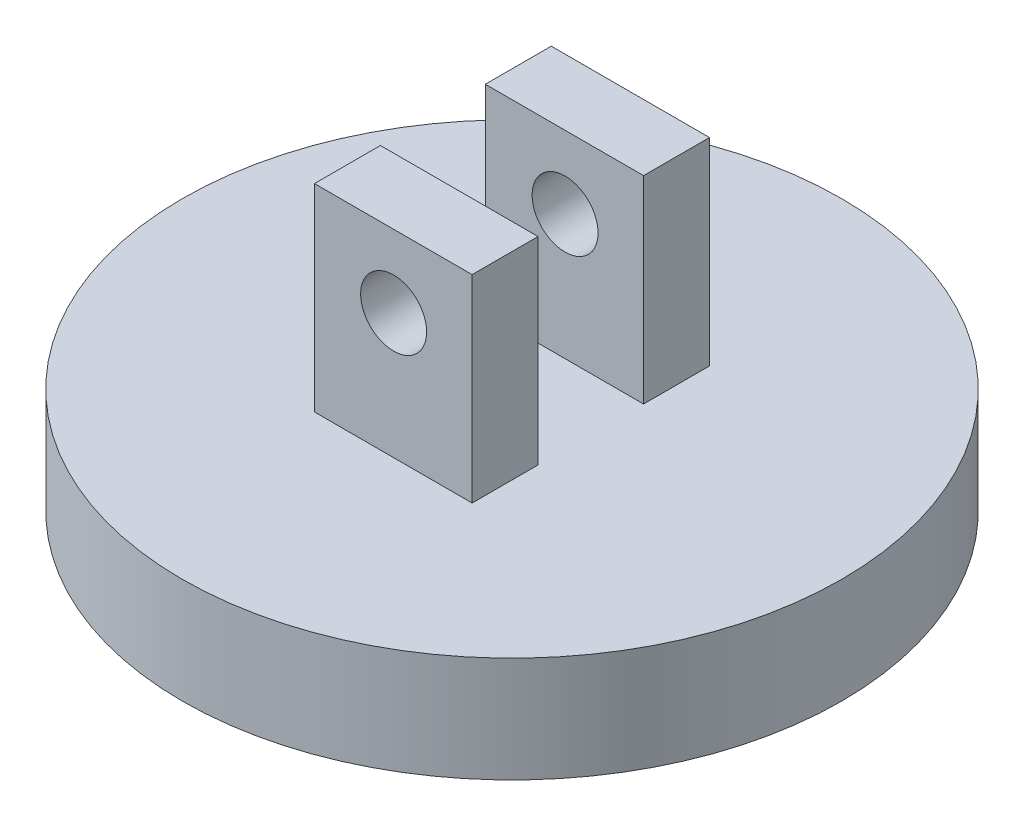
SolidWorks part; units mm, degrees
ref_plane "Front Plane" through (0, 0, 0) normal (0, 0, 1) x (1, 0, 0)
ref_plane "Top Plane" through (0, 0, 0) normal (0, 1, 0) x (1, 0, 0)
ref_plane "Right Plane" through (0, 0, 0) normal (1, 0, 0) x (0, 0, -1)
sketch "Sketch1" plane through (0, 0, 0) normal (0, 1, 0) x (1, 0, 0)
  circle A0 centre (0, 0) radius 250
  dimension "D1" = 500
extrude "Boss-Extrude1" add sketch "Sketch1" along normal blind 80
sketch "Sketch2" plane through (0, 80, 0) normal (0, 1, 0) x (1, 0, 0)
  line L1 (-60.2364, 90) -> (59.7636, 90)
  line L2 (-60.2364, 90) -> (-60.2364, 40)
  line L3 (-60.2364, 40) -> (59.7636, 40)
  line L4 (59.7636, 90) -> (59.7636, 40)
  line L5 (-60.2364, 90) -> (59.7636, 40) construction
  line L6 (-60.2364, 40) -> (59.7636, 90) construction
  line L7 (-59.7636, -90) -> (59.7636, -90)
  line L8 (-59.7636, -90) -> (-59.7636, -40)
  line L9 (-59.7636, -40) -> (59.7636, -40)
  line L10 (59.7636, -90) -> (59.7636, -40)
  line L11 (-59.7636, -90) -> (59.7636, -40) construction
  line L12 (-59.7636, -40) -> (59.7636, -90) construction
  point P0 (-0.2364, 65)
  point P6 (0, -65)
  dimension "D5" = 40
  dimension "D1" = 120
  dimension "D2" = 50
  dimension "D3" = 50
  dimension "D4" = 40
extrude "Boss-Extrude2" add sketch "Sketch2" along normal blind 150
sketch "Sketch3" plane through (0, 0, 90) normal (0, 0, 1) x (1, 0, 0)
  line L0 (-59.7636, 230) -> (59.7636, 230) construction
  line L2 (-59.7636, 230) -> (-59.7636, 80) construction
  circle A0 centre (0.2364, 175) radius 25
  dimension "D1" = 50
  dimension "D2" = 55
  dimension "D3" = 60
extrude "Cut-Extrude1" cut sketch "Sketch3" against normal through all
